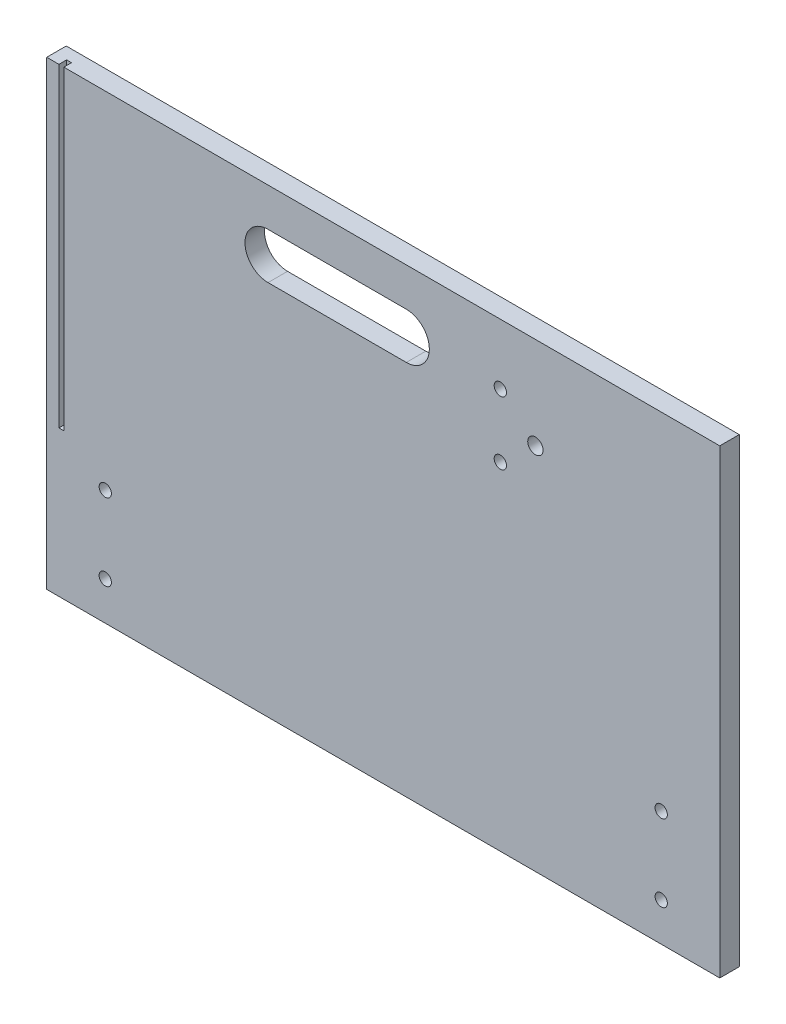
SolidWorks part; units mm, degrees
ref_plane "Front Plane" through (0, 0, 0) normal (0, 0, 1) x (1, 0, 0)
ref_plane "Top Plane" through (0, 0, 0) normal (0, 1, 0) x (1, 0, 0)
ref_plane "Right Plane" through (0, 0, 0) normal (1, 0, 0) x (0, 0, -1)
sketch "Sketch1" plane through (0, 0, 0) normal (0, 0, 1) x (1, 0, 0)
  line L1 (219.05, -150) -> (-219.05, -150)
  line L2 (219.05, -150) -> (219.05, 150) construction
  line L3 (219.05, 150) -> (-219.05, 150)
  line L4 (-219.05, -150) -> (-219.05, 150) construction
  line L5 (219.05, -150) -> (-219.05, 150) construction
  line L6 (219.05, 150) -> (-219.05, -150) construction
  line L8 (0, 150) -> (0, -150) construction
  line L11 (-219.05, 150) -> (-219.05, -150)
  line L12 (219.05, 150) -> (219.05, -150)
  point P0 (0, 0)
  dimension "D1" = 438.1
  dimension "D4" = 300
extrude "Boss-Extrude1" add sketch "Sketch1" along normal blind 12.7
sketch "Sketch2" plane through (0, 0, 12.7) normal (0, 0, 1) x (1, 0, 0)
  line L0 (99.05, 150) -> (99.05, -150) construction
  line L1 (219.05, 150) -> (-219.05, 150) construction
  line L2 (219.05, -150) -> (-219.05, -150) construction
  line L3 (219.05, 150) -> (219.05, -150) construction
  line L4 (219.05, 90) -> (-219.05, 90) construction
  line L5 (-219.05, 150) -> (-219.05, -150) construction
  circle A0 centre (76.2149, 110.5901) radius 4
  circle A1 centre (99.05, 90) radius 5
  line B0 (99.05, 111.9118) -> (99.05, 68.0882) construction
  line B1 (84.024, 105.026) -> (114.076, 74.974) construction
  line B2 (99.05, 120.052) -> (68.998, 90)
  line B3 (99.05, 120.052) -> (129.102, 90)
  line B4 (129.102, 90) -> (99.05, 59.948) construction
  line B5 (68.998, 90) -> (99.05, 59.948)
  line B6 (99.05, 120.052) -> (99.05, 59.948) construction
  line B7 (129.102, 90) -> (68.998, 90) construction
  line B8 (120.44, 81.3379) -> (126.0968, 75.6811)
  line B9 (114.076, 74.974) -> (119.7329, 69.3171) construction
  line B10 (126.0968, 75.6811) -> (113.3689, 62.9532)
  line B11 (107.7121, 68.61) -> (113.3689, 62.9532)
  line B12 (129.102, 90) -> (120.44, 81.3379)
  line B13 (99.05, 59.948) -> (107.7121, 68.61)
  line B14 (128.7485, 90.3536) -> (128.7485, 89.6464)
  circle B15 centre (76.2149, 110.5901) radius 4
  circle B16 centre (76.2149, 69.4099) radius 4
  line B17 (74.7026, 94.9282) -> (94.1218, 114.3474) construction
  line B18 (103.9782, 114.3474) -> (123.3974, 94.9282) construction
  line B19 (123.3974, 85.0718) -> (103.9782, 65.6526) construction
  line B20 (94.1218, 65.6526) -> (74.7026, 85.0718) construction
  circle B21 centre (120.9618, 90) radius 1.5541 construction
  arc B22 (74.7026, 85.0718) -> (74.7026, 94.9282) centre (99.05, 90) cw construction
  arc B23 (94.1218, 114.3474) -> (103.9782, 114.3474) centre (99.05, 90) cw construction
  arc B24 (123.3974, 94.9282) -> (123.3974, 85.0718) centre (99.05, 90) cw construction
  arc B25 (103.9782, 65.6526) -> (94.1218, 65.6526) centre (99.05, 90) cw construction
  circle B26 centre (99.05, 90) radius 13.462 construction
  circle B27 centre (99.05, 68.0882) radius 1.5541 construction
  circle B28 centre (77.1382, 90) radius 1.5541 construction
  circle B29 centre (99.05, 111.9118) radius 1.5541 construction
  line B30 (101.2951, 121.9435) -> (96.8049, 117.4534) construction
  line B31 (96.8049, 117.4534) -> (128.7485, 85.5099) construction
  line B32 (128.7485, 94.4901) -> (101.2951, 121.9435) construction
  line B33 (128.7485, 94.4901) -> (96.8049, 62.5466) construction
  line B34 (96.8049, 62.5466) -> (101.2951, 58.0565) construction
  line B35 (101.2951, 58.0565) -> (128.7485, 85.5099) construction
  line B36 (96.8049, 117.4534) -> (69.3515, 117.4534) construction
  line B37 (69.3515, 117.4534) -> (69.3515, 62.5466) construction
  line B38 (96.8049, 62.5466) -> (69.3515, 62.5466) construction
  circle B39 centre (76.2149, 69.4099) radius 4 construction
  circle B40 centre (76.2149, 110.5901) radius 4 construction
  circle B41 centre (99.05, 90) radius 13.462 construction
  circle B42 centre (99.05, 111.9118) radius 1.5541 construction
  circle B43 centre (120.9618, 90) radius 1.5541 construction
  circle B44 centre (99.05, 68.0882) radius 1.5541 construction
  circle B45 centre (77.1382, 90) radius 1.5541 construction
  dimension "D3" = 10
  dimension "D1" = 120
  dimension "D2" = 60
sketch_block_instance "Block1-2"
sketch_block "Block1" parameters "D1"=42.5, "D2"=8, "D3"=18
sketch_block_instance "nema 17 mount dxf-1"
sketch_block "nema 17 mount dxf"
sketch_block_instance "Fold pattern - Angle Mount v3-1"
sketch_block "Fold pattern - Angle Mount v3"
extrude "Cut-Extrude1" cut sketch "Sketch2" against normal up to next contours B16 | A0 | A1
sketch "Sketch3" plane through (0, 0, 12.7) normal (0, 0, 1) x (1, 0, 0)
  line L0 (219.05, 150) -> (-219.05, 150) construction
  line L1 (-211.1125, 150) -> (-207.9375, 150)
  line L2 (-211.1125, 150) -> (-211.1125, -55)
  line L3 (-211.1125, -55) -> (-207.9375, -55)
  line L4 (-207.9375, 150) -> (-207.9375, -55)
  line L5 (-209.525, 150) -> (-209.525, -55) construction
  line L6 (-219.05, 150) -> (-219.05, -150) construction
  line L7 (219.05, -150) -> (-219.05, -150) construction
  dimension "D1" = 3.175
  dimension "D2" = 9.525
  dimension "D3" = 95
extrude "Cut-Extrude2" cut sketch "Sketch3" against normal blind 5
sketch "Sketch4" plane through (0, 0, 12.7) normal (0, 0, 1) x (1, 0, 0)
  line L0 (-219.05, -50) -> (219.05, -50) construction
  line L1 (-219.05, 150) -> (-219.05, -150) construction
  line L2 (219.05, 150) -> (219.05, -150) construction
  line L3 (219.05, -150) -> (-219.05, -150) construction
  line L4 (-206.35, -100) -> (-155.55, -100) construction
  line L5 (-219.05, -50) -> (-206.35, -50) construction
  line L6 (-219.05, -50) -> (-219.05, -150) construction
  line L7 (-219.05, -150) -> (-206.35, -150) construction
  line L8 (-206.35, -50) -> (-206.35, -150) construction
  line L9 (-206.35, -150) -> (-155.55, -150) construction
  line L10 (-206.35, -150) -> (-206.35, -50) construction
  line L11 (-206.35, -50) -> (-155.55, -50) construction
  line L12 (-155.55, -150) -> (-155.55, -50) construction
  line L13 (-180.95, -100) -> (-180.95, -50) construction
  line L14 (0, -50) -> (0, -150) construction
  line L15 (180.95, -100) -> (180.95, -50) construction
  line L16 (155.55, -150) -> (155.55, -50) construction
  line L17 (206.35, -50) -> (155.55, -50) construction
  line L18 (206.35, -150) -> (206.35, -50) construction
  line L19 (206.35, -150) -> (155.55, -150) construction
  line L20 (206.35, -50) -> (206.35, -150) construction
  line L21 (219.05, -150) -> (206.35, -150) construction
  line L22 (219.05, -50) -> (219.05, -150) construction
  line L23 (219.05, -50) -> (206.35, -50) construction
  line L24 (206.35, -100) -> (155.55, -100) construction
  circle A0 centre (-180.95, -75) radius 4
  circle A1 centre (-180.95, -125) radius 4
  circle A2 centre (180.95, -125) radius 4
  circle A3 centre (180.95, -75) radius 4
  dimension "D4" = 8
  dimension "D1" = 100
  dimension "D2" = 12.7
  dimension "D3" = 50.8
extrude "Cut-Extrude3" cut sketch "Sketch4" against normal up to next
sketch "Sketch5" plane through (0, 0, 12.7) normal (0, 0, 1) x (1, 0, 0)
  line L0 (15, 110) -> (-75, 110) construction
  line L1 (15, 95) -> (-75, 95)
  line L2 (15, 125) -> (-75, 125)
  line L3 (219.05, 150) -> (-207.9375, 150) construction
  arc A0 (15, 95) -> (15, 125) centre (15, 110) ccw
  arc A1 (-75, 125) -> (-75, 95) centre (-75, 110) ccw
  point P2 (-30, 110)
  dimension "D2" = 15
  dimension "D1" = 40
  dimension "D3" = 90
  dimension "D4" = 30
extrude "Cut-Extrude4" cut sketch "Sketch5" against normal up to next
